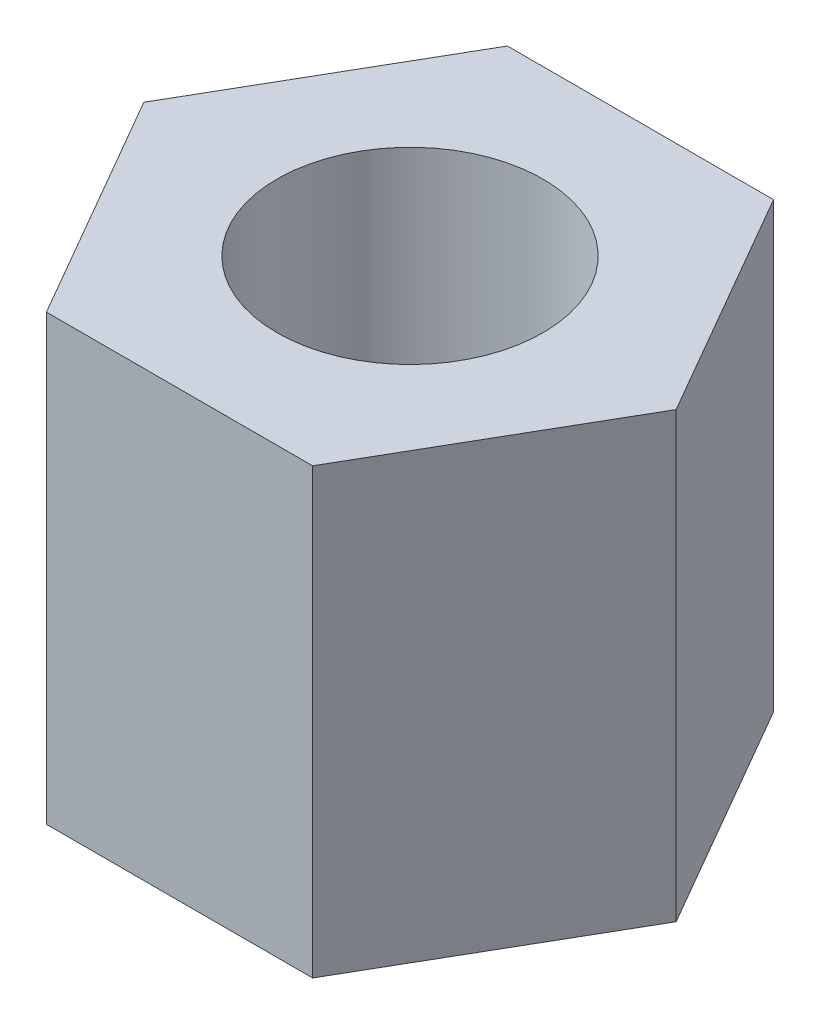
SolidWorks part; units mm, degrees
ref_plane "前视基准面" through (0, 0, 0) normal (0, 0, 1) x (1, 0, 0)
ref_plane "上视基准面" through (0, 0, 0) normal (0, 1, 0) x (1, 0, 0)
ref_plane "右视基准面" through (0, 0, 0) normal (1, 0, 0) x (0, 0, -1)
other "Configuration Table"
sketch "草图1" plane through (0, 0, 0) normal (0, 1, 0) x (1, 0, 0)
  line L1 (-6, 0) -> (-3, -5.1962)
  line L2 (-3, -5.1962) -> (3, -5.1962)
  line L3 (3, -5.1962) -> (6, 0)
  line L4 (6, 0) -> (3, 5.1962)
  line L5 (3, 5.1962) -> (-3, 5.1962)
  line L6 (-3, 5.1962) -> (-6, 0)
  circle A0 centre (0, 0) radius 5.1962 construction
  circle A1 centre (0, 0) radius 3
  point P10 (5.986, 0)
extrude "凸台-拉伸1" add sketch "草图1" along normal blind 10
